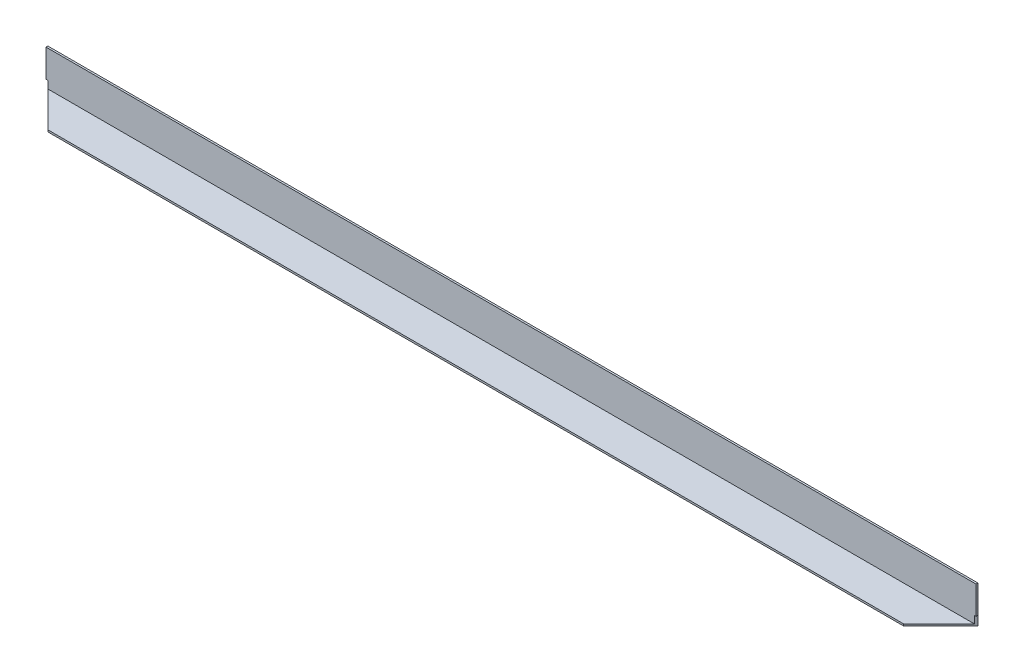
SolidWorks part; units mm, degrees
other "Markup1"
sketch "Sketch5" plane through (-348.8746, 66.7203, 40) normal (-0.6639, 0.4507, 0.5967) x (0.6003, -0.1547, 0.7847)
ref_plane "Front Plane" through (0, 0, 0) normal (0, 0, 1) x (1, 0, 0)
ref_plane "Top Plane" through (0, 0, 0) normal (0, 1, 0) x (1, 0, 0)
ref_plane "Right Plane" through (0, 0, 0) normal (1, 0, 0) x (0, 0, -1)
sketch "Sketch2" plane through (0, 0, 0) normal (0, 0, 1) x (1, 0, 0)
  line L1 (-348.8746, 66.7203) -> (651.1254, 66.7203)
  line L2 (-348.8746, 66.7203) -> (-348.8746, 26.7203)
  line L3 (-348.8746, 26.7203) -> (651.1254, 26.7203)
  line L4 (651.1254, 66.7203) -> (651.1254, 26.7203)
  dimension "D1" = 1000
  dimension "D2" = 40
extrude "Boss-Extrude1" add sketch "Sketch2" along normal blind 40
sketch "Sketch3" plane through (-348.8746, 0, 0) normal (-1, 0, 0) x (0, 0, 1)
  line L0 (0, 66.7203) -> (0, 26.7203) construction
  line L1 (2, 66.7203) -> (40, 66.7203)
  line L2 (2, 66.7203) -> (2, 28.7203)
  line L3 (2, 28.7203) -> (40, 28.7203)
  line L4 (40, 66.7203) -> (40, 28.7203)
  line L5 (40, 26.7203) -> (0, 26.7203) construction
  line L6 (40, 66.7203) -> (40, 26.7203) construction
  line L7 (40, 66.7203) -> (0, 66.7203) construction
  dimension "D1" = 2
  dimension "D2" = 2
  dimension "D3" = 0
  dimension "D4" = 0
extrude "Cut-Extrude1" cut sketch "Sketch3" against normal blind 1004
sketch "Sketch4" plane through (0, 26.7203, 0) normal (0, -1, 0) x (-1, 0, 0)
  line L0 (-651.1254, 0) -> (-651.1254, -40)
  line L1 (-651.1254, 0) -> (-611.1254, -40)
  line L2 (348.8746, -40) -> (-651.1254, -40) construction
  line L3 (-611.1254, -40) -> (-651.1254, -40)
  line L4 (348.8746, 0) -> (308.8746, -40)
  line L5 (308.8746, -40) -> (348.8746, -40)
  line L6 (348.8746, -40) -> (348.8746, 0)
  dimension "D1" = 40
  dimension "D2" = 40
extrude "Cut-Extrude2" cut sketch "Sketch4" against normal blind 10
